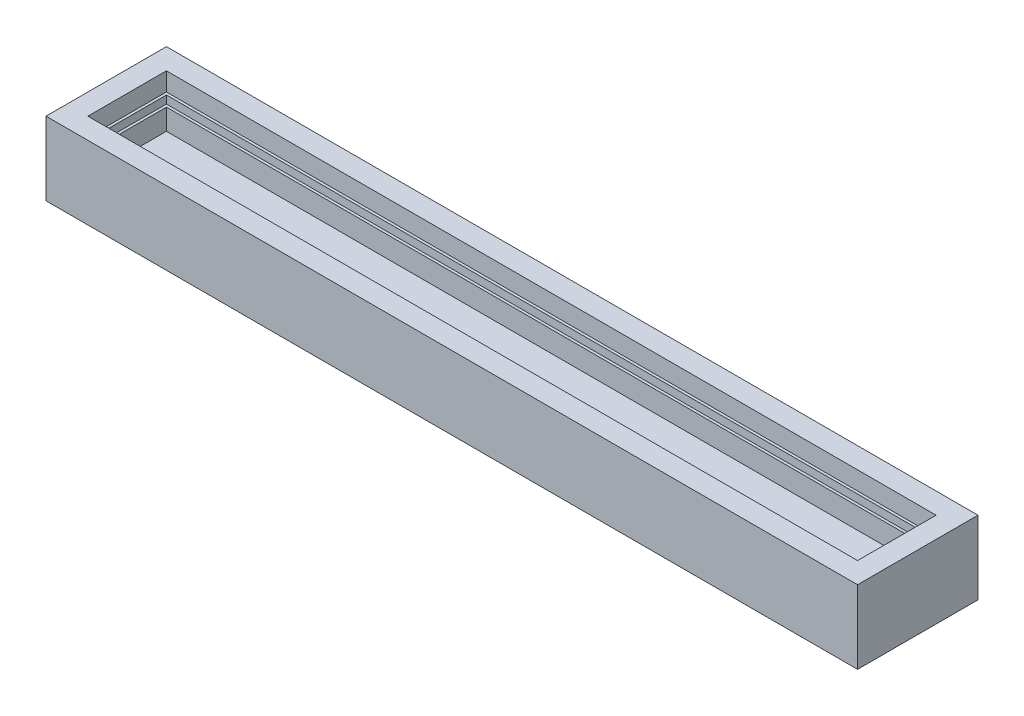
SolidWorks part; units mm, degrees
ref_plane "Ebene vorne" through (0, 0, 0) normal (0, 0, 1) x (1, 0, 0)
ref_plane "Ebene oben" through (0, 0, 0) normal (0, 1, 0) x (1, 0, 0)
ref_plane "Ebene rechts" through (0, 0, 0) normal (1, 0, 0) x (0, 0, -1)
sketch "Skizze1" plane through (0, 0, 0) normal (0, 1, 0) x (1, 0, 0)
  line L1 (-77.5, -11.5) -> (77.5, -11.5)
  line L2 (-77.5, -11.5) -> (-77.5, 11.5)
  line L3 (-77.5, 11.5) -> (77.5, 11.5)
  line L4 (77.5, -11.5) -> (77.5, 11.5)
  line L5 (-77.5, -11.5) -> (77.5, 11.5) construction
  line L6 (-77.5, 11.5) -> (77.5, -11.5) construction
  line L7 (-73.5, -7.5) -> (73.5, -7.5)
  line L8 (-73.5, -7.5) -> (-73.5, 7.5)
  line L9 (-73.5, 7.5) -> (73.5, 7.5)
  line L10 (73.5, -7.5) -> (73.5, 7.5)
  line L11 (-73.5, -7.5) -> (73.5, 7.5) construction
  line L12 (-73.5, 7.5) -> (73.5, -7.5) construction
  point P0 (0, 0)
  point P6 (0, 0)
  dimension "D1" = 4
  dimension "D2" = 4
  dimension "D3" = 155
  dimension "D4" = 23
extrude "Aufsatz-Linear austragen1" add sketch "Skizze1" along normal blind 10
sketch "Skizze3" plane through (0, 0, 0) normal (0, -1, 0) x (1, 0, 0)
  line L4 (77.5, -11.5) -> (77.5, 11.5)
  line L5 (77.5, 11.5) -> (-77.5, 11.5)
  line L6 (-77.5, 11.5) -> (-77.5, -11.5)
  line L7 (-77.5, -11.5) -> (77.5, -11.5)
  line L8 (77.5, -11.5) -> (77.5, 11.5)
  line L9 (77.5, 11.5) -> (-77.5, 11.5)
  line L10 (-77.5, 11.5) -> (-77.5, -11.5)
  line L11 (-77.5, -11.5) -> (77.5, -11.5)
  dimension "D1" = 0
extrude "Aufsatz-Linear austragen3" add sketch "Skizze3" along normal blind 4
ref_plane "Ebene1" through (0, 4, 0) normal (0, 1, 0) x (1, 0, 0)
sketch "Skizze4" plane through (0, 4, 0) normal (0, 1, 0) x (1, 0, 0)
  line L0 (-74.5, 8.5) -> (-74.5, -8.5)
  line L1 (-74.5, -8.5) -> (74.5, -8.5)
  line L2 (74.5, -8.5) -> (74.5, 8.5)
  line L3 (74.5, 8.5) -> (-74.5, 8.5)
  line L4 (-73.5, 7.5) -> (-73.5, -7.5)
  line L5 (-73.5, -7.5) -> (73.5, -7.5)
  line L6 (73.5, -7.5) -> (73.5, 7.5)
  line L7 (73.5, 7.5) -> (-73.5, 7.5)
  line L8 (-73.5, 7.5) -> (-73.5, -7.5)
  line L9 (-73.5, -7.5) -> (73.5, -7.5)
  line L10 (73.5, -7.5) -> (73.5, 7.5)
  line L11 (73.5, 7.5) -> (-73.5, 7.5)
  dimension "D1" = 0
  dimension "D2" = 1
extrude "Schnitt-Linear austragen1" cut sketch "Skizze4" along normal blind 0.5
ref_plane "Ebene2" through (0, 6, 0) normal (0, 1, 0) x (1, 0, 0)
sketch "Skizze5" plane through (0, 6, 0) normal (0, 1, 0) x (1, 0, 0)
  line L4 (74.5, 8.5) -> (-74.5, 8.5)
  line L5 (-74.5, 8.5) -> (-74.5, -8.5)
  line L6 (-74.5, -8.5) -> (74.5, -8.5)
  line L7 (74.5, -8.5) -> (74.5, 8.5)
  line L8 (74.5, 8.5) -> (-74.5, 8.5)
  line L9 (-74.5, 8.5) -> (-74.5, -8.5)
  line L10 (-74.5, -8.5) -> (74.5, -8.5)
  line L11 (74.5, -8.5) -> (74.5, 8.5)
  dimension "D1" = 0
extrude "Schnitt-Linear austragen2" cut sketch "Skizze5" along normal blind 0.5
